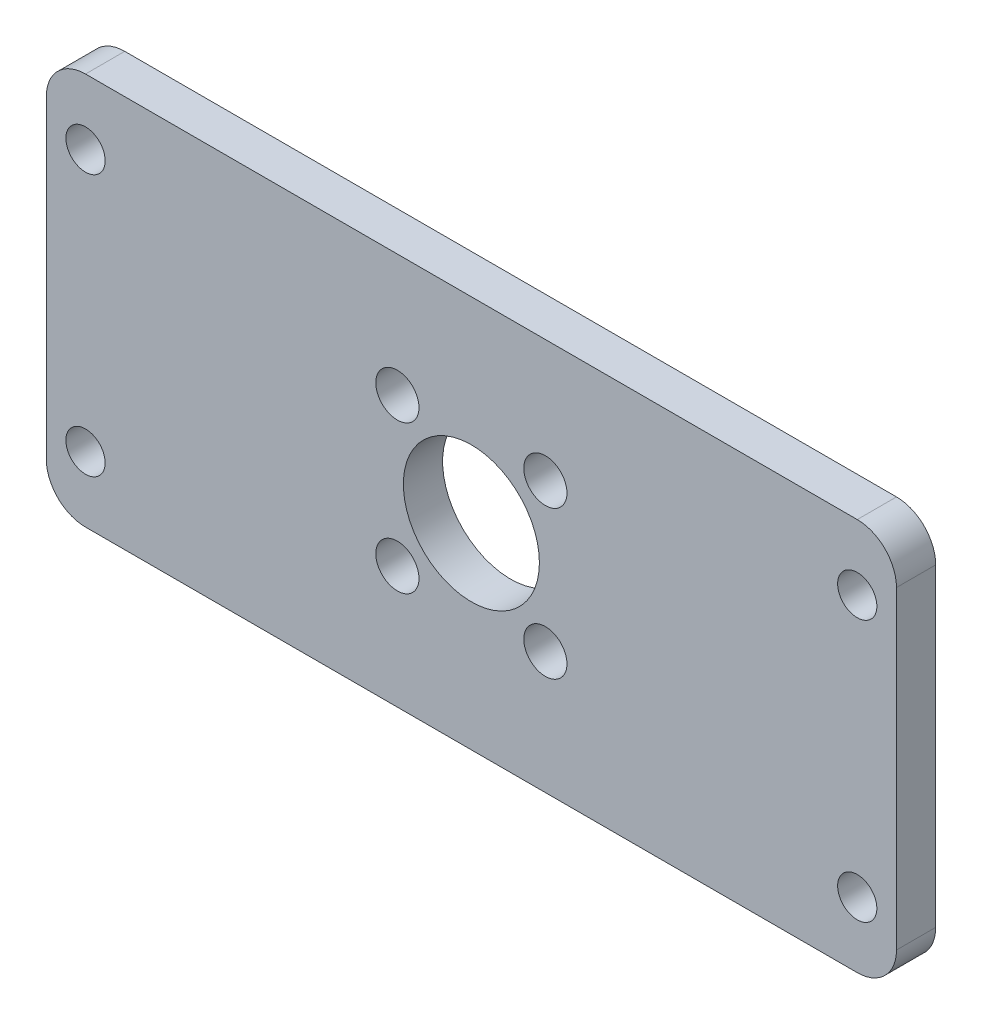
SolidWorks part; units mm, degrees
ref_plane "前视基准面" through (0, 0, 0) normal (0, 0, 1) x (1, 0, 0)
ref_plane "上视基准面" through (0, 0, 0) normal (0, 1, 0) x (1, 0, 0)
ref_plane "右视基准面" through (0, 0, 0) normal (1, 0, 0) x (0, 0, -1)
other "Configuration Table"
sketch "草图1" plane through (0, 0, 0) normal (0, 0, 1) x (1, 0, 0)
  line L0 (0, 0) -> (-8, 0) construction
  line L1 (0, 0) -> (-5.6569, 5.6569) construction
  line L3 (-32.5, -20) -> (32.5, -20)
  line L4 (-32.5, -20) -> (-32.5, 20)
  line L5 (-32.5, 20) -> (32.5, 20)
  line L6 (32.5, -20) -> (32.5, 20)
  line L7 (-32.5, -20) -> (32.5, 20) construction
  line L8 (-32.5, 20) -> (32.5, -20) construction
  circle A0 centre (0, 0) radius 8 construction
  circle A1 centre (-5.6569, 5.6569) radius 1.65
  circle A2 centre (0, 0) radius 5.2
  circle A3 centre (5.6569, 5.6569) radius 1.65
  circle A4 centre (5.6569, -5.6569) radius 1.65
  circle A5 centre (-5.6569, -5.6569) radius 1.65
  point P16 (0, 0)
  dimension "D1" = 16
  dimension "D2" = 10.4
  dimension "D3" = 3.3
  dimension "D4" = 45
  dimension "D6" = 65
  dimension "D7" = 40
  dimension "D5" = 4
extrude "凸台-拉伸1" add sketch "草图1" along normal blind 3
sketch "草图2" plane through (0, 0, 3) normal (0, 0, 1) x (1, 0, 0)
  line L0 (32.5, -20) -> (32.5, 20) construction
  line L1 (-29.5, -10) -> (29.5, -10) construction
  line L2 (-29.5, -10) -> (-29.5, 10) construction
  line L3 (-29.5, 10) -> (29.5, 10) construction
  line L4 (29.5, -10) -> (29.5, 10) construction
  line L5 (-32.5, 20) -> (-32.5, -20) construction
  line L6 (-32.5, -20) -> (32.5, -20) construction
  circle A0 centre (29.5, 10) radius 1.5
  circle A1 centre (29.5, -10) radius 1.5
  circle A2 centre (-29.5, -10) radius 1.5
  circle A3 centre (-29.5, 10) radius 1.5
  dimension "D5" = 3
  dimension "D1" = 20
  dimension "D2" = 3
  dimension "D3" = 3
  dimension "D4" = 10
extrude "切除-拉伸1" cut sketch "草图2" against normal blind 3
sketch "草图3" plane through (0, 0, 0) normal (0, 0, -1) x (-1, 0, 0)
  line L0 (32.5, 20) -> (32.5, -20) construction
  line L1 (-32.5, 20) -> (32.5, 20)
  line L2 (-32.5, 20) -> (-32.5, 15)
  line L3 (-32.5, 15) -> (32.5, 15)
  line L4 (32.5, 20) -> (32.5, 15)
  dimension "D1" = 5
extrude "切除-拉伸2" cut sketch "草图3" against normal blind 10
sketch "草图4" plane through (0, 0, 3) normal (0, 0, 1) x (1, 0, 0)
  line L0 (32.5, -20) -> (32.5, 15) construction
  line L1 (-32.5, -20) -> (32.5, -20)
  line L2 (-32.5, -20) -> (-32.5, -15)
  line L3 (-32.5, -15) -> (32.5, -15)
  line L4 (32.5, -20) -> (32.5, -15)
  dimension "D1" = 5
extrude "切除-拉伸3" cut sketch "草图4" against normal blind 10
fillet "圆角2" radius 3 4 edges at (32.5, 15, 1.5) (32.5, -15, 1.5) (-32.5, -15, 1.5) (-32.5, 15, 1.5)
